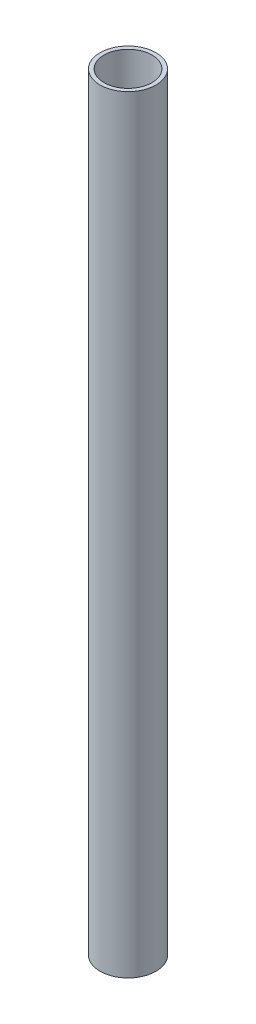
SolidWorks part; units mm, degrees
ref_plane "Front Plane" through (0, 0, 0) normal (0, 0, 1) x (1, 0, 0)
ref_plane "Top Plane" through (0, 0, 0) normal (0, 1, 0) x (1, 0, 0)
ref_plane "Right Plane" through (0, 0, 0) normal (1, 0, 0) x (0, 0, -1)
sketch "Sketch1" plane through (0, 0, 0) normal (0, 1, 0) x (1, 0, 0)
  circle A0 centre (0, 0) radius 38.1
  circle A1 centre (0, 0) radius 44.45
  dimension "D1" = 76.2
  dimension "D2" = 88.9
extrude "Boss-Extrude1" add sketch "Sketch1" along normal mid plane 1219.2
